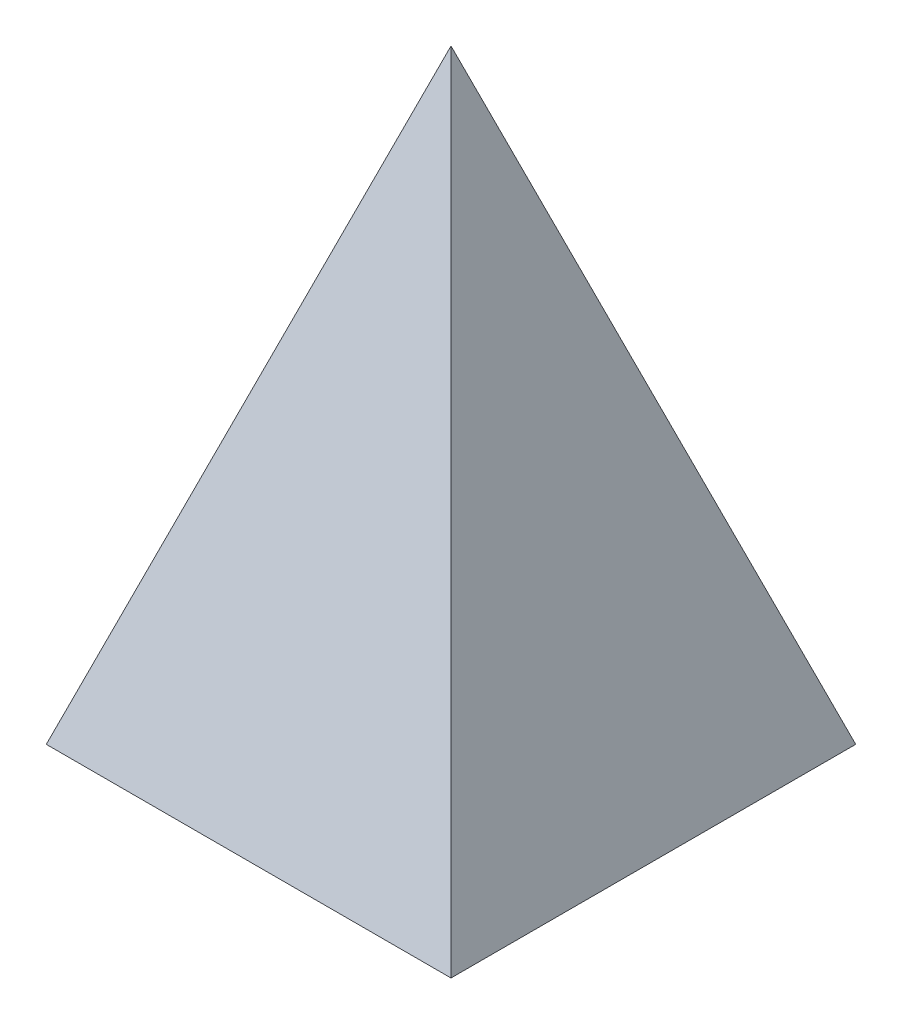
SolidWorks part; units mm, degrees
ref_plane "前视基准面" through (0, 0, 0) normal (0, 0, 1) x (1, 0, 0)
ref_plane "上视基准面" through (0, 0, 0) normal (0, 1, 0) x (1, 0, 0)
ref_plane "右视基准面" through (0, 0, 0) normal (1, 0, 0) x (0, 0, -1)
sketch "草图1" plane through (0, 0, 0) normal (0, 1, 0) x (1, 0, 0)
  line L1 (0, 0) -> (50, 0)
  line L2 (0, 0) -> (0, 50)
  line L3 (0, 50) -> (50, 50)
  line L4 (50, 0) -> (50, 50)
extrude "凸台-拉伸1" add sketch "草图1" along normal blind 75 draft 18.5
